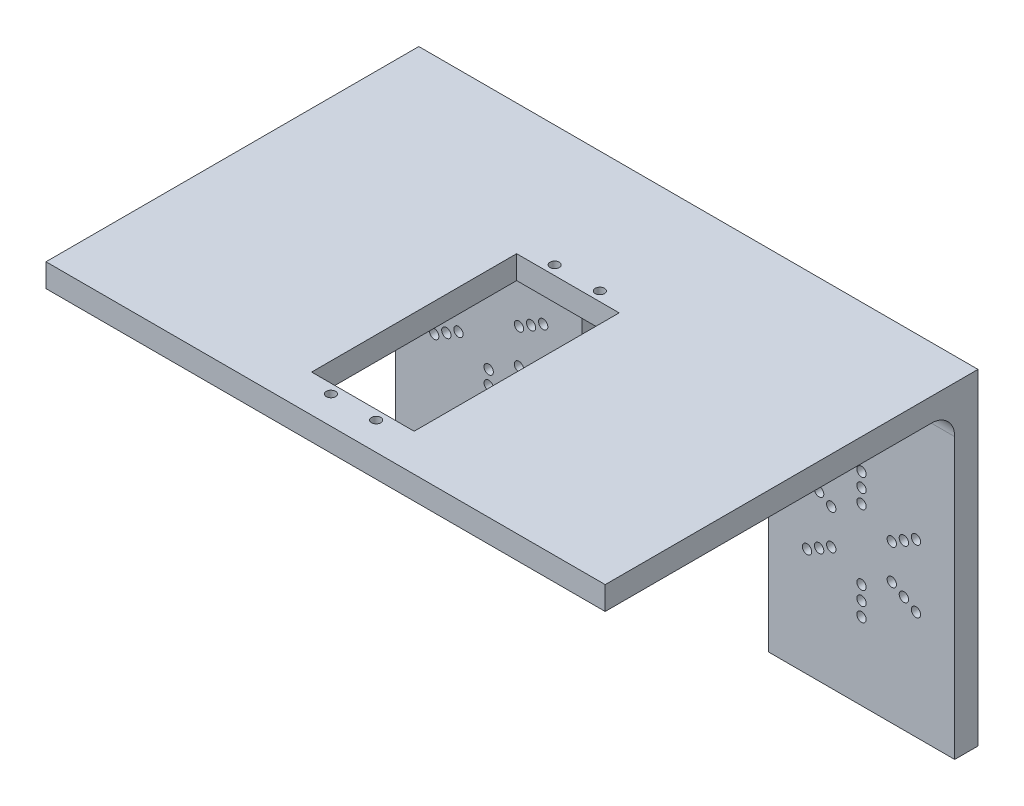
SolidWorks part; units mm, degrees
material "Polylactic Acid"
ref_plane "Front Plane" through (0, 0, 0) normal (0, 0, 1) x (1, 0, 0)
ref_plane "Top Plane" through (0, 0, 0) normal (0, 1, 0) x (1, 0, 0)
ref_plane "Right Plane" through (0, 0, 0) normal (1, 0, 0) x (0, 0, -1)
sketch "Sketch1" plane through (0, 0, 0) normal (0, 1, 0) x (1, 0, 0)
  line L0 (-4.85, -24) -> (4.85, -24) construction
  line L5 (-60, 30) -> (60, 30)
  line L6 (-60, 30) -> (-60, -30)
  line L8 (60, 30) -> (60, -30)
  line L9 (-60, 30) -> (60, -30) construction
  line L10 (-60, -30) -> (60, 30) construction
  line L11 (-11, 22) -> (11, 22)
  line L12 (-11, 22) -> (-11, -22)
  line L13 (-11, -22) -> (11, -22)
  line L14 (11, 22) -> (11, -22)
  line L15 (-11, 22) -> (11, -22) construction
  line L16 (-11, -22) -> (11, 22) construction
  line L17 (-4.85, -24) -> (-4.85, 24) construction
  line L19 (60, -30) -> (-60, -30)
  line L24 (-60, 30) -> (60, 30)
  line L25 (-60, 30) -> (-60, 50)
  line L26 (-60, 50) -> (60, 50)
  line L27 (60, 30) -> (60, 50)
  circle A0 centre (-4.85, -24) radius 1
  circle A1 centre (4.85, -24) radius 1
  circle A2 centre (4.85, 24) radius 1
  circle A3 centre (-4.85, 24) radius 1
  point P0 (0, 0)
  point P5 (0, 0)
  point P12 (0, -24)
  point P13 (0, -22)
  point P14 (-4.85, 0)
  point P24 (-11, 0)
  dimension "D7" = 48
  dimension "D3" = 22
  dimension "D9" = 2
  dimension "D1" = 60
  dimension "D2" = 120
  dimension "D5" = 2
  dimension "D6" = 9.7
  dimension "D10" = 20
  dimension "D4" = 44
  dimension "D8" = 2
extrude "Boss-Extrude1" add sketch "Sketch1" along normal mid plane 70
sketch "Sketch2" plane through (-60, 0, -85) normal (1, 0, 0) x (0, 0, -1)
  line L22 (-40, -35) -> (-115, -35)
  line L23 (-40, -35) -> (-40, 30)
  line L24 (-40, 30) -> (-115, 30)
  line L25 (-115, -35) -> (-115, 30)
  line L27 (-35, 35) -> (-115, 35) construction
  line L28 (-35, 35) -> (-35, -35) construction
  dimension "D1" = 5
  dimension "D2" = 5
extrude "Cut-Extrude1" cut sketch "Sketch2" along normal up to surface (120 mm away) up to face at (60, 0, -10)
sketch "Sketch3" plane through (0, 0, -50) normal (0, 0, -1) x (-1, 0, 0)
  line L0 (60, -35) -> (-60, -35) construction
  line L1 (-20, -35) -> (20, -35)
  line L2 (-20, -35) -> (-20, 30)
  line L3 (-20, 30) -> (20, 30)
  line L4 (20, -35) -> (20, 30)
  line L5 (60, 35) -> (-60, 35) construction
  point P6 (0, 30)
  point P9 (0, 35)
  dimension "D1" = 40
  dimension "D2" = 5
extrude "Cut-Extrude2" cut sketch "Sketch3" against normal up to surface (5 mm away) up to face at (0, -2.5, -45)
fillet "Fillet1" radius 5 4 edges at (40, 30, -45) (20, 30, -47.5) (-20, 30, -47.5) (-40, 30, -45)
sketch "Sketch4" plane through (0, 0, -45) normal (0, 0, 1) x (1, 0, 0)
  line L0 (-40, -18.5) -> (-40, -15.5) construction
  line L1 (-40, -5) -> (-40, -12.5) construction
  line L2 (-60, -35) -> (-60, 25) construction
  line L3 (-20, -35) -> (-60, -35) construction
  line L4 (40, -18.5) -> (40, -15.5) construction
  line L5 (40, -5) -> (40, -12.5) construction
  line L6 (-40, -18.5) -> (40, -18.5) construction
  line L7 (60, -35) -> (20, -35) construction
  circle A0 centre (-40, -18.5) radius 1
  circle A1 centre (-40, -15.5) radius 1
  circle A2 centre (-40, -12.5) radius 1
  circle A3 centre (-46.4952, -8.75) radius 1
  circle A4 centre (-49.0933, -10.25) radius 1
  circle A5 centre (-51.6913, -11.75) radius 1
  circle A6 centre (-46.4952, -1.25) radius 1
  circle A7 centre (-49.0933, 0.25) radius 1
  circle A8 centre (-51.6913, 1.75) radius 1
  circle A9 centre (-40, 2.5) radius 1
  circle A10 centre (-40, 5.5) radius 1
  circle A11 centre (-40, 8.5) radius 1
  circle A12 centre (-33.5048, -1.25) radius 1
  circle A13 centre (-30.9067, 0.25) radius 1
  circle A14 centre (-28.3087, 1.75) radius 1
  circle A15 centre (-33.5048, -8.75) radius 1
  circle A16 centre (-30.9067, -10.25) radius 1
  circle A17 centre (-28.3087, -11.75) radius 1
  circle A18 centre (40, -18.5) radius 1
  circle A19 centre (40, -15.5) radius 1
  circle A20 centre (40, -12.5) radius 1
  circle A21 centre (33.5048, -8.75) radius 1
  circle A22 centre (30.9067, -10.25) radius 1
  circle A23 centre (28.3087, -11.75) radius 1
  circle A24 centre (33.5048, -1.25) radius 1
  circle A25 centre (30.9067, 0.25) radius 1
  circle A26 centre (28.3087, 1.75) radius 1
  circle A27 centre (40, 2.5) radius 1
  circle A28 centre (40, 5.5) radius 1
  circle A29 centre (40, 8.5) radius 1
  circle A30 centre (46.4952, -1.25) radius 1
  circle A31 centre (49.0933, 0.25) radius 1
  circle A32 centre (51.6913, 1.75) radius 1
  circle A33 centre (46.4952, -8.75) radius 1
  circle A34 centre (49.0933, -10.25) radius 1
  circle A35 centre (51.6913, -11.75) radius 1
  point P43 (-60, -5)
  point P48 (-40, -35)
  point P92 (40, -35)
  dimension "D3" = 2
  dimension "D2" = 3
  dimension "D5" = 7.5
  dimension "D1" = 3
  dimension "D4" = 6
extrude "Cut-Extrude3" cut sketch "Sketch4" against normal up to surface (5 mm away) up to face at (0, 4.2071, -50)
